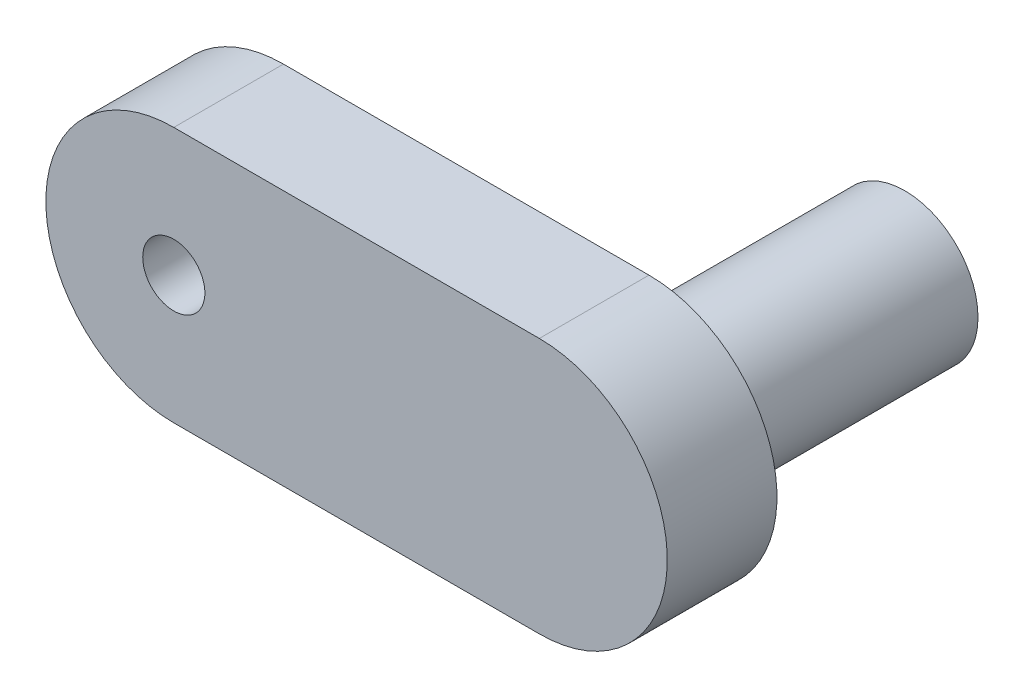
SolidWorks part; units mm, degrees
ref_plane "Plano frontal" through (0, 0, 0) normal (0, 0, 1) x (1, 0, 0)
ref_plane "Plano superior" through (0, 0, 0) normal (0, 1, 0) x (1, 0, 0)
ref_plane "Plano direito" through (0, 0, 0) normal (1, 0, 0) x (0, 0, -1)
sketch "Esboço1" plane through (0, 0, 0) normal (0, 0, 1) x (1, 0, 0)
  line L0 (0, 0) -> (10, 0) construction
  line L1 (0, 3.5) -> (10, 3.5)
  line L2 (0, -3.5) -> (10, -3.5)
  arc A0 (0, 3.5) -> (0, -3.5) centre (0, 0) ccw
  arc A1 (10, -3.5) -> (10, 3.5) centre (10, 0) ccw
  point P3 (5, 0)
  dimension "D1" = 10
  dimension "D2" = 7
extrude "Ressalto-extrusão1" add sketch "Esboço1" along normal mid plane 3
sketch "Esboço2" plane through (0, 0, -1.5) normal (0, 0, -1) x (-1, 0, 0)
  circle A0 centre (-10, 0) radius 2
  arc A2 (-10, 3.5) -> (-10, -3.5) centre (-10, 0) ccw construction
  dimension "D1" = 4
extrude "Ressalto-extrusão2" add sketch "Esboço2" along normal blind 7
sketch "Esboço3" plane through (0, 0, -1.5) normal (0, 0, -1) x (-1, 0, 0)
  circle A0 centre (0, 0) radius 0.85
  dimension "D1" = 1.7
extrude "Corte-extrusão1" cut sketch "Esboço3" against normal up to next
